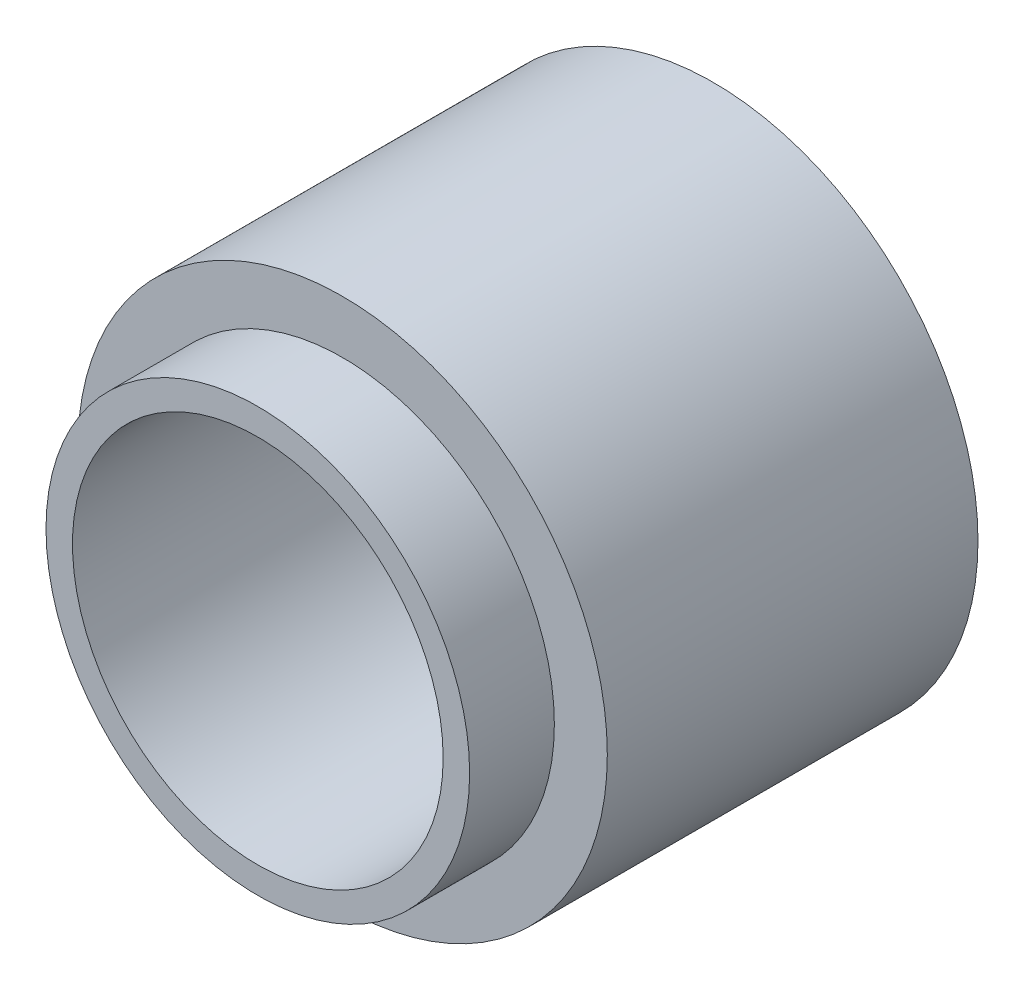
SolidWorks part; units mm, degrees
ref_plane "Front Plane" through (0, 0, 0) normal (0, 0, 1) x (1, 0, 0)
ref_plane "Top Plane" through (0, 0, 0) normal (0, 1, 0) x (1, 0, 0)
ref_plane "Right Plane" through (0, 0, 0) normal (1, 0, 0) x (0, 0, -1)
sketch "Sketch1" plane through (0, 0, 0) normal (0, 0, 1) x (1, 0, 0)
  circle A0 centre (0, 0) radius 5
  dimension "D1" = 10
extrude "Boss-Extrude1" add sketch "Sketch1" along normal blind 7
sketch "Sketch2" plane through (0, 0, 7) normal (0, 0, 1) x (1, 0, 0)
  circle A0 centre (0, 0) radius 3.5
  dimension "7" = 7
extrude "Cut-Extrude1" cut sketch "Sketch2" against normal through all contours A0
sketch "Sketch3" plane through (0, 0, 7) normal (0, 0, 1) x (1, 0, 0)
  circle A0 centre (0, 0) radius 4
  circle A2 centre (0, 0) radius 3.5 construction
  circle A3 centre (0, 0) radius 3.5
  dimension "D1" = 8
extrude "Boss-Extrude4" add sketch "Sketch3" along normal blind 1.6
